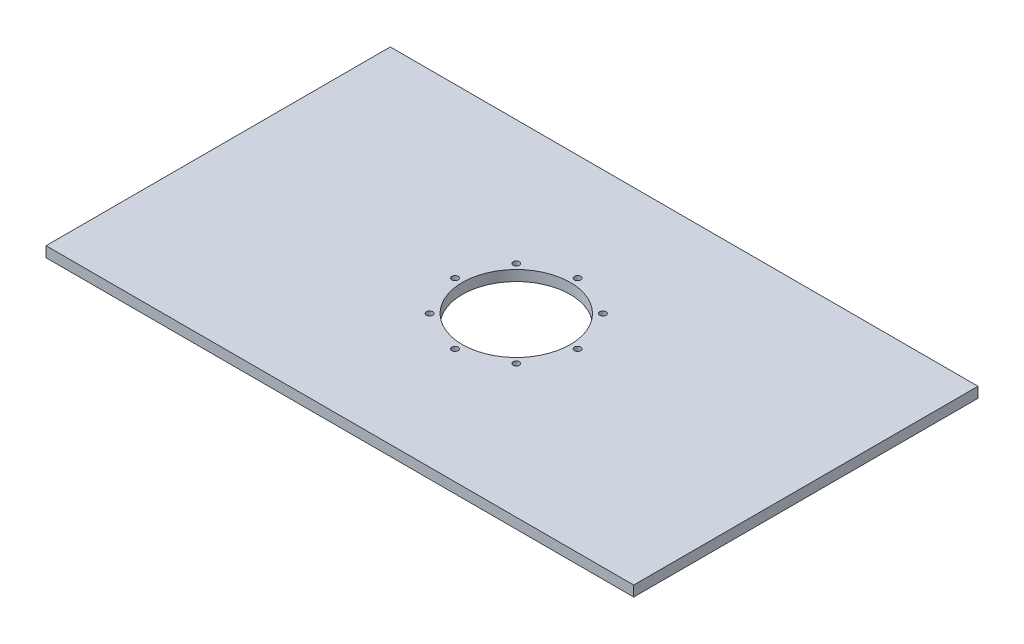
SolidWorks part; units mm, degrees
ref_plane "Front Plane" through (0, 0, 0) normal (0, 0, 1) x (1, 0, 0)
ref_plane "Top Plane" through (0, 0, 0) normal (0, 1, 0) x (1, 0, 0)
ref_plane "Right Plane" through (0, 0, 0) normal (1, 0, 0) x (0, 0, -1)
sketch "Sketch1" plane through (0, 0, 0) normal (0, 1, 0) x (1, 0, 0)
  line L0 (84.5, 140.2627) -> (84.5, -38.7989) construction
  line L1 (0, 0) -> (169, 0)
  line L2 (0, 0) -> (0, 99)
  line L3 (0, 99) -> (169, 99)
  line L4 (169, 0) -> (169, 99)
  circle A1 centre (84.5, 50.7319) radius 15.5
  circle A2 centre (84.5, 68.3569) radius 0.905
  circle A3 centre (96.9628, 63.1946) radius 0.905
  circle A4 centre (102.125, 50.7319) radius 0.905
  circle A5 centre (96.9628, 38.2691) radius 0.905
  circle A6 centre (84.5, 33.1069) radius 0.905
  circle A7 centre (72.0372, 38.2691) radius 0.905
  circle A8 centre (66.875, 50.7319) radius 0.905
  circle A9 centre (72.0372, 63.1946) radius 0.905
  dimension "D4" = 31
  dimension "D5" = 1.81
  dimension "D1" = 99
  dimension "D2" = 169
  dimension "D6" = 8
extrude "Boss-Extrude4" add sketch "Sketch1" along normal blind 3 contours A1 | L2 L1 L4 L3 | A6 | A5 | A4 | A3 | A2 | A9 | A8 | A7
